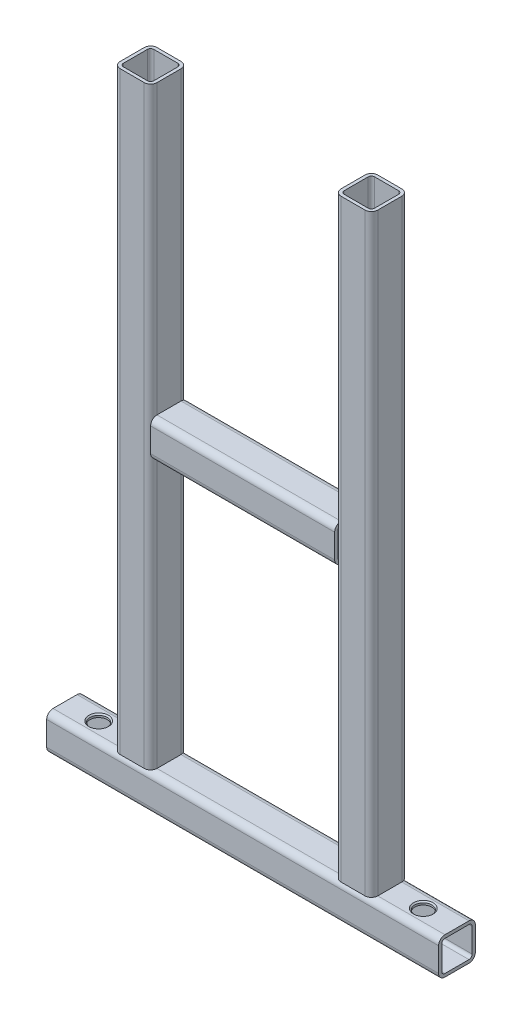
SolidWorks part; units mm, degrees
material "AISI 304"
ref_plane "Ön Düzlem" through (0, 0, 0) normal (0, 0, 1) x (1, 0, 0)
ref_plane "Üst Düzlem" through (0, 0, 0) normal (0, 1, 0) x (1, 0, 0)
ref_plane "Sağ Düzlem" through (0, 0, 0) normal (1, 0, 0) x (0, 0, -1)
sketch "Sketch1" plane through (0, 0, 0) normal (0, 0, 1) x (1, 0, 0)
  line L0 (-90.13, 0) -> (90.13, 0)
  line L1 (-90.13, 0) -> (-90.13, -500)
  line L2 (0, 0) -> (0, -64.4447) construction
  line L3 (90.13, 0) -> (90.13, -500)
  line L4 (-90.13, -250) -> (90.13, -250)
  line L5 (-160, -500) -> (160, -500)
  point P4 (0, 0)
  point P14 (0, -500)
  dimension "D1" = 180.26
  dimension "D2" = 500
  dimension "D3" = 320
other "Square tube 30 X 30 X 2.6(1)"
ref_plane "Plane1" through (-90.13, 0, 0) normal (0, -1, 0) x (1, 0, 0)
sketch "Sketch17" plane through (-90.13, 0, 0) normal (0, -1, 0) x (1, 0, 0)
  line L0 (-9.8, -12.4) -> (9.8, -12.4)
  line L1 (-12.4, -9.8) -> (-12.4, 9.8)
  line L2 (9.8, 12.4) -> (-9.8, 12.4)
  line L3 (12.4, 9.8) -> (12.4, -9.8)
  line L4 (-9.8, -15) -> (9.8, -15)
  line L5 (-15, -9.8) -> (-15, 9.8)
  line L6 (9.8, 15) -> (-9.8, 15)
  line L7 (15, 9.8) -> (15, -9.8)
  arc A0 (15, 9.8) -> (9.8, 15) centre (9.8, 9.8) ccw
  arc A1 (9.8, -15) -> (15, -9.8) centre (9.8, -9.8) ccw
  arc A2 (-15, -9.8) -> (-9.8, -15) centre (-9.8, -9.8) ccw
  arc A3 (-9.8, 15) -> (-15, 9.8) centre (-9.8, 9.8) ccw
  arc A4 (-9.8, 12.4) -> (-12.4, 9.8) centre (-9.8, 9.8) ccw
  arc A5 (12.4, 9.8) -> (9.8, 12.4) centre (9.8, 9.8) ccw
  arc A6 (9.8, -12.4) -> (12.4, -9.8) centre (9.8, -9.8) ccw
  arc A7 (-12.4, -9.8) -> (-9.8, -12.4) centre (-9.8, -9.8) ccw
  point P0 (-15, 0)
  point P1 (15, 0)
  point P2 (0, 15)
  point P3 (0, -15)
  point P4 (0, 0)
  point P5 (-15, -15)
  point P6 (15, -15)
  point P7 (15, 15)
  point P8 (-15, 15)
  point P33 (0, 0)
  dimension "D1" = 5.2
  dimension "Thickness" = 2.6
  dimension "V_leg" = 30
sketch "Sketch12" plane through (0, -485, 0) normal (0, 1, 0) x (1, 0, 0)
  line L0 (-160, 0) -> (-105.13, 0) construction
  line L1 (-160, 9.8) -> (-160, -9.8) construction
  line L2 (-105.13, -9.8) -> (-105.13, 9.8) construction
hole_wizard "M16 Tapped Hole1" positions "Sketch18" profile "Sketch19" tap size "M16" standard "ISO"
sketch "Sketch18" plane through (0, -485, 0) normal (0, 1, 0) x (1, 0, 0)
  line L0 (-160, 0) -> (-105.13, 0) construction
  point P0 (-132.565, 0)
sketch "Sketch19" plane through (-132.565, -485, 0) normal (1, 0, 0) x (0, 0, 1)
  line L0 (0, 0) -> (0, 42.206)
  line L1 (0, 42.206) -> (7, 38)
  line L2 (7, 38) -> (7, 1.025)
  line L3 (7, 1.025) -> (8.025, 0)
  line L5 (8.025, 0) -> (0, 0)
  line L6 (-7, 1.025) -> (-8.025, 0) construction
  line L10 (0, 42.206) -> (-7, 38) construction
  line L11 (0, -6.35) -> (0, 107.95) construction
  dimension "Tap Drill Dia." = 14
  dimension "Tap Drill Depth" = 38
  dimension "Near C'Sink Dia." = 16.05
  dimension "Near C'Sink Angle" = 90
  dimension "Drill Angle" = 118
cosmetic thread "Hole Thread1" parameters "D1"=32, "D2"=16
mirror "Mirror1" about plane through (0, 0, 0) normal (1, 0, 0) of "M16 Tapped Hole1"
cosmetic thread "Hole Thread2" parameters "D1"=32, "D2"=16
